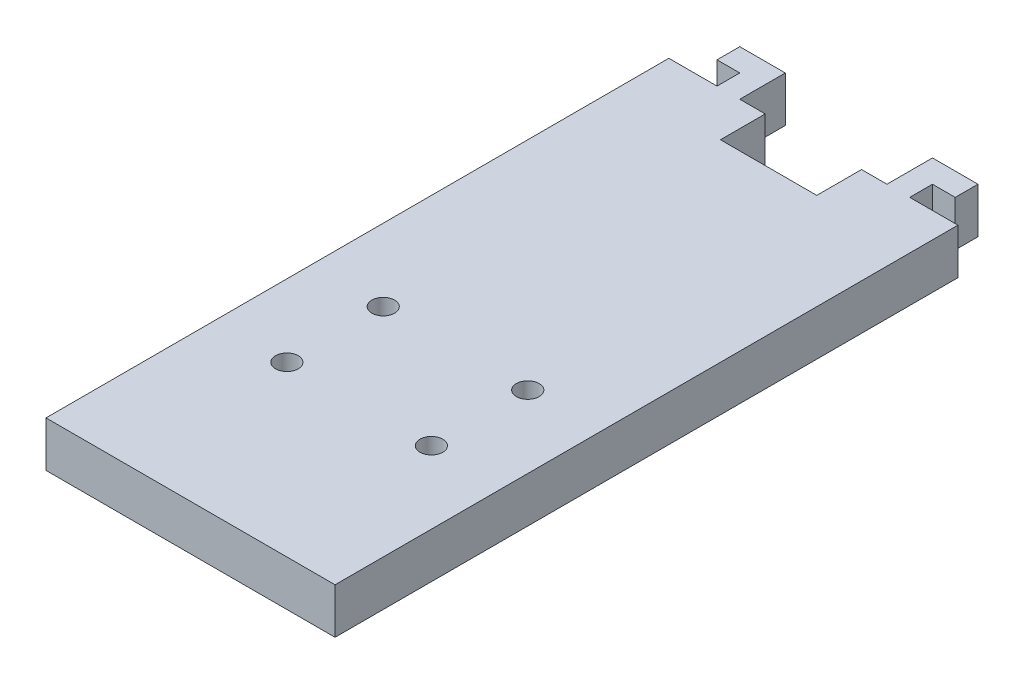
SolidWorks part; units mm, degrees
ref_plane "Front Plane" through (0, 0, 0) normal (0, 0, 1) x (1, 0, 0)
ref_plane "Top Plane" through (0, 0, 0) normal (0, 1, 0) x (1, 0, 0)
ref_plane "Right Plane" through (0, 0, 0) normal (1, 0, 0) x (0, 0, -1)
sketch "Sketch1" plane through (0, 0, 0) normal (0, 1, 0) x (1, 0, 0)
  line L0 (12.7, 44) -> (12.7, 47)
  line L1 (-19.05, -38.1) -> (19.05, -38.1)
  line L2 (-19.05, -38.1) -> (-19.05, 38.1)
  line L3 (-6.35, 38.1) -> (6.35, 38.1)
  line L4 (19.05, -38.1) -> (19.05, 38.1)
  line L5 (-19.05, -38.1) -> (19.05, 38.1) construction
  line L6 (-19.05, 38.1) -> (19.05, -38.1) construction
  line L7 (-6.35, 44) -> (-19.05, 44)
  line L8 (-6.35, 44) -> (-6.35, 38.1)
  line L9 (-6.35, 38.1) -> (-19.05, 38.1) construction
  line L10 (-19.05, 44) -> (-19.05, 38.1)
  line L11 (-6.35, 44) -> (-19.05, 38.1) construction
  line L12 (-6.35, 38.1) -> (-19.05, 44) construction
  line L13 (6.35, 44) -> (19.05, 44)
  line L14 (6.35, 44) -> (6.35, 38.1)
  line L15 (6.35, 38.1) -> (19.05, 38.1) construction
  line L16 (19.05, 44) -> (19.05, 38.1)
  line L17 (6.35, 44) -> (19.05, 38.1) construction
  line L18 (6.35, 38.1) -> (19.05, 44) construction
  line L19 (-9.7, 50) -> (-15.7, 50)
  line L20 (-9.7, 50) -> (-9.7, 44)
  line L21 (-9.7, 44) -> (-15.7, 44)
  line L22 (-15.7, 50) -> (-15.7, 47)
  line L23 (-9.7, 50) -> (-15.7, 44) construction
  line L24 (-9.7, 44) -> (-15.7, 50) construction
  line L25 (15.7, 50) -> (9.7, 50)
  line L26 (15.7, 50) -> (15.7, 47)
  line L27 (15.7, 44) -> (9.7, 44)
  line L28 (9.7, 50) -> (9.7, 44)
  line L29 (15.7, 50) -> (9.7, 44) construction
  line L30 (15.7, 44) -> (9.7, 50) construction
  line L31 (12.7, 47) -> (15.7, 47)
  line L32 (-12.7, 44) -> (-12.7, 47)
  line L33 (-12.7, 47) -> (-15.7, 47)
  line L34 (-15.7, 47) -> (-15.7, 44) construction
  line L35 (15.7, 47) -> (15.7, 44) construction
  line L36 (6.35, 38.1) -> (19.05, 38.1) construction
  line L37 (-19.05, 38.1) -> (-6.35, 38.1) construction
  point P0 (0, 0)
  point P6 (-12.7, 41.05)
  point P7 (12.7, 41.05)
  point P11 (-12.7, 47)
  point P19 (12.7, 47)
  dimension "D1" = 12.7
  dimension "D2" = 25.4
  dimension "D3" = 5.9
  dimension "D4" = 76.2
  dimension "D5" = 6
  dimension "D6" = 6
  dimension "D7" = 3
  dimension "D8" = 3
extrude "Boss-Extrude1" add sketch "Sketch1" along normal mid plane 6 contours L16 L13 L14 L3 L8 L7 L21 L10 L2 L1 L4 | L33 L32 L7 L20 L19 L22 | L0 L31 L26 L25 L28 L13
sketch "Sketch2" plane through (0, 3, 0) normal (0, 1, 0) x (1, 0, 0)
  line L1 (9.525, -15.875) -> (-9.525, -15.875) construction
  line L2 (9.525, -15.875) -> (9.525, -3.175) construction
  line L3 (9.525, -3.175) -> (-9.525, -3.175) construction
  line L4 (-9.525, -15.875) -> (-9.525, -3.175) construction
  line L5 (9.525, -15.875) -> (-9.525, -3.175) construction
  line L6 (9.525, -3.175) -> (-9.525, -15.875) construction
  line L7 (-6.35, 38.1) -> (6.35, 38.1) construction
  circle A0 centre (-9.525, -3.175) radius 1.5
  circle A1 centre (9.525, -3.175) radius 1.5
  circle A2 centre (9.525, -15.875) radius 1.5
  circle A3 centre (-9.525, -15.875) radius 1.5
  point P0 (0, -9.525)
  dimension "D1" = 3
  dimension "D2" = 19.05
  dimension "D3" = 12.7
  dimension "D4" = 47.625
extrude "Cut-Extrude1" cut sketch "Sketch2" against normal through all both and the other way through all
equation "\"D1@Boss-Extrude1\"=6mm"
equation "\"D3@Sketch1\"=6mm-.1mm"
